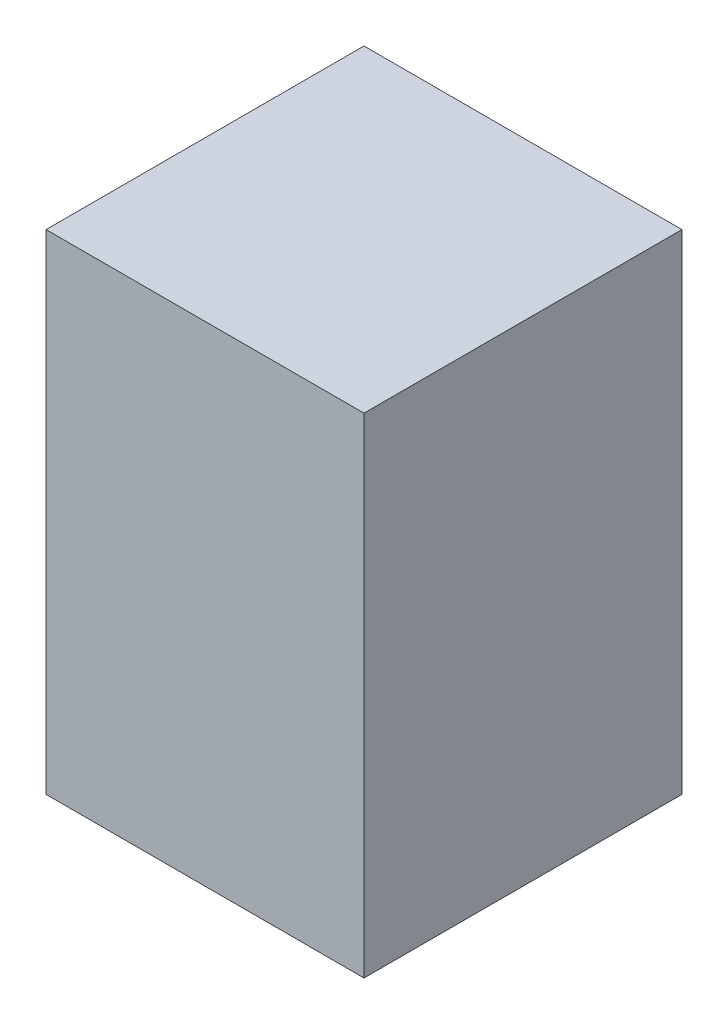
SolidWorks part; units mm, degrees
material "Ceramic Porcelain"
ref_plane "Front Plane" through (0, 0, 0) normal (0, 0, 1) x (1, 0, 0)
ref_plane "Top Plane" through (0, 0, 0) normal (0, 1, 0) x (1, 0, 0)
ref_plane "Right Plane" through (0, 0, 0) normal (1, 0, 0) x (0, 0, -1)
sketch "Sketch1" plane through (0, 0, 0) normal (0, 1, 0) x (1, 0, 0)
  line L1 (0, 0) -> (6.5, 0)
  line L2 (0, 0) -> (0, 6.5)
  line L3 (0, 6.5) -> (6.5, 6.5)
  line L4 (6.5, 0) -> (6.5, 6.5)
  dimension "D1" = 6.5
  dimension "D2" = 6.5
extrude "Boss-Extrude1" add sketch "Sketch1" along normal blind 10
